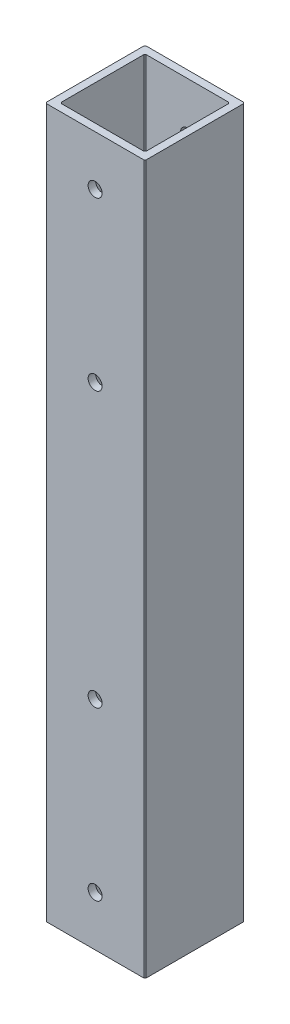
SolidWorks part; units mm, degrees
ref_plane "Front Plane" through (0, 0, 0) normal (0, 0, 1) x (1, 0, 0)
ref_plane "Top Plane" through (0, 0, 0) normal (0, 1, 0) x (1, 0, 0)
ref_plane "Right Plane" through (0, 0, 0) normal (1, 0, 0) x (0, 0, -1)
ref_plane "Plane1" through (0, 0, 180) normal (0, 0, 1) x (1, 0, 0)
sketch "Sketch1" plane through (0, 0, 180) normal (0, 0, 1) x (1, 0, 0)
  line L0 (-120, -142) -> (-80, -142)
  line L1 (-80, -142) -> (-80, 142)
  line L2 (-80, 142) -> (-120, 142)
  line L3 (-120, 142) -> (-120, -142)
extrude "Boss-Extrude1" add sketch "Sketch1" against normal blind 40
sketch "Sketch2" plane through (0, -142, 0) normal (0, -1, 0) x (1, 0, 0)
  line L0 (-83, 143) -> (-83, 177)
  line L1 (-83, 177) -> (-117, 177)
  line L2 (-117, 177) -> (-117, 143)
  line L3 (-117, 143) -> (-83, 143)
extrude "Cut-Extrude1" cut sketch "Sketch2" against normal through all
hole_wizard "Ø5.6 (5.6) Diameter Hole1" positions "Sketch4" profile "Sketch3" hole size "Ø5.6" standard "ANSI Metric"
sketch "Sketch4" plane through (0, 0, 140) normal (0, 0, -1) x (-1, 0, 0)
  point P0 (100, 122)
  point P1 (100, 55)
  point P2 (100, -55)
  point P3 (100, -122)
sketch "Sketch3" plane through (-100, 122, 140) normal (1, 0, 0) x (0, 1, 0)
  line L0 (0, 0) -> (0, 3)
  line L1 (0, 3) -> (2.8, 3)
  line L2 (2.8, 3) -> (2.8, 0)
  line L5 (2.8, 0) -> (0, 0)
  line L11 (0, -6.35) -> (0, 107.95) construction
  dimension "Thru Hole Dia." = 5.6
  dimension "Thru Hole Depth" = 3
hole_wizard "Ø5.6 (5.6) Diameter Hole2" positions "Sketch6" profile "Sketch5" hole size "Ø5.6" standard "ANSI Metric"
sketch "Sketch6" plane through (0, 0, 177) normal (0, 0, -1) x (-1, 0, 0)
  point P0 (100, 122)
  point P1 (100, 55)
  point P2 (100, -55)
  point P3 (100, -122)
sketch "Sketch5" plane through (-100, 122, 177) normal (1, 0, 0) x (0, 1, 0)
  line L0 (0, 0) -> (0, 3)
  line L1 (0, 3) -> (2.8, 3)
  line L2 (2.8, 3) -> (2.8, 0)
  line L5 (2.8, 0) -> (0, 0)
  line L11 (0, -6.35) -> (0, 107.95) construction
  dimension "Thru Hole Dia." = 5.6
  dimension "Thru Hole Depth" = 3
chamfer "Chamfer1" distance 0.5 angle 45 8 edges at (-80, 0, 140) (-120, 0, 140) (-120, 0, 180) (-117, 0, 177) (-80, 0, 180) (-83, 0, 143) (-83, 0, 177) (-117, 0, 143)
